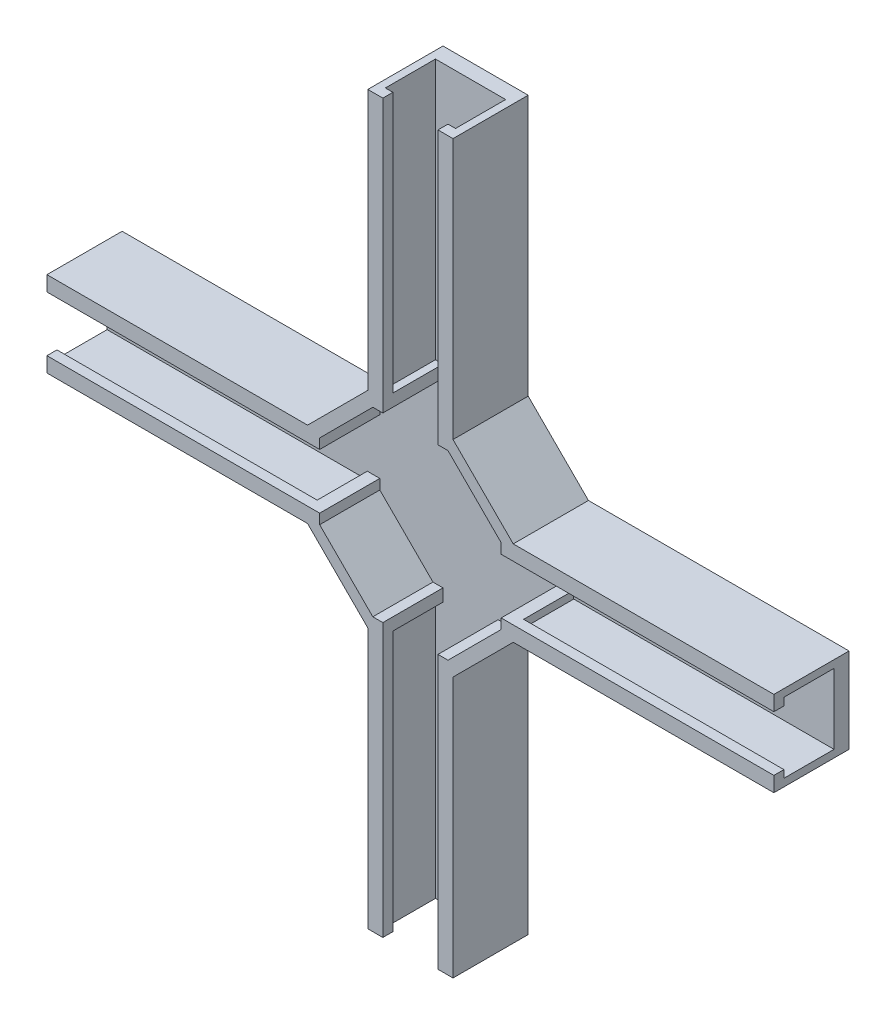
SolidWorks part; units mm, degrees
ref_plane "Спереди" through (0, 0, 0) normal (0, 0, 1) x (1, 0, 0)
ref_plane "Сверху" through (0, 0, 0) normal (0, 1, 0) x (1, 0, 0)
ref_plane "Справа" through (0, 0, 0) normal (1, 0, 0) x (0, 0, -1)
sketch "Эскиз1" plane through (0, 0, 0) normal (0, 0, 1) x (1, 0, 0)
  line L0 (20.5208, 8.5) -> (20.5208, -8.5)
  line L1 (8.5, 20.5208) -> (-8.5, 20.5208)
  line L2 (-8.5, 20.5208) -> (-20.5208, 8.5)
  line L3 (-20.5208, 8.5) -> (-20.5208, -8.5)
  line L4 (-20.5208, -8.5) -> (-8.5, -20.5208)
  line L5 (-8.5, -20.5208) -> (8.5, -20.5208)
  line L6 (8.5, -20.5208) -> (20.5208, -8.5)
  line L7 (20.5208, -8.5) -> (20.5208, 8.5)
  line L8 (20.5208, 8.5) -> (8.5, 20.5208)
  line L9 (20.5208, 8.5) -> (72.5208, 8.5)
  line L10 (20.5208, -8.5) -> (72.5208, -8.5)
  line L11 (72.5208, 8.5) -> (72.5208, -8.5)
  line L12 (-8.5, -20.5208) -> (8.5, -20.5208)
  line L13 (-8.5, -20.5208) -> (-8.5, -72.5208)
  line L14 (8.5, -20.5208) -> (8.5, -72.5208)
  line L15 (-8.5, -72.5208) -> (8.5, -72.5208)
  line L16 (-20.5208, -8.5) -> (-20.5208, 8.5)
  line L17 (-20.5208, -8.5) -> (-72.5208, -8.5)
  line L18 (-20.5208, 8.5) -> (-72.5208, 8.5)
  line L19 (-72.5208, -8.5) -> (-72.5208, 8.5)
  line L20 (-8.5, 20.5208) -> (8.5, 20.5208)
  line L21 (-8.5, 20.5208) -> (-8.5, 72.5208)
  line L22 (8.5, 20.5208) -> (8.5, 72.5208)
  line L23 (-8.5, 72.5208) -> (8.5, 72.5208)
  circle A0 centre (0, 0) radius 20.5208 construction
  dimension "D1" = 52
  dimension "D2" = 52
  dimension "D3" = 52
  dimension "D4" = 52
  dimension "D6" = 17
extrude "Бобышка-Вытянуть1" add sketch "Эскиз1" along normal blind 15 contours L19 L17 L3 L18 | L0 L8 L1 L2 L3 L4 L5 L6 | L23 L21 L1 L22 | L11 L9 L0 L10 | L13 L15 L14 L5
sketch "Эскиз8" plane through (0, 0, 15) normal (0, 0, 1) x (1, 0, 0)
  line L0 (-18.1066, 5.5) -> (-72.5208, 5.5)
  line L1 (18.1066, 7.5) -> (7.5, 18.1066)
  line L2 (7.5, 18.1066) -> (-7.5, 18.1066)
  line L3 (-7.5, 18.1066) -> (-18.1066, 7.5)
  line L4 (-18.1066, 7.5) -> (-18.1066, -7.5)
  line L5 (-18.1066, -7.5) -> (-7.5, -18.1066)
  line L6 (-7.5, -18.1066) -> (7.5, -18.1066)
  line L7 (7.5, -18.1066) -> (18.1066, -7.5)
  line L8 (18.1066, -7.5) -> (18.1066, 7.5)
  line L9 (-18.1066, 5.5) -> (-18.1066, -5.5)
  line L10 (-72.5208, 5.5) -> (-72.5208, -5.5)
  line L11 (-18.1066, -5.5) -> (-72.5208, -5.5)
  line L12 (-72.5208, -8.5) -> (-72.5208, 8.5) construction
  line L13 (-20.5208, 8.5) -> (-72.5208, 8.5) construction
  line L14 (-20.5208, -8.5) -> (-72.5208, -8.5) construction
  line L15 (72.5208, 8.5) -> (72.5208, -8.5) construction
  line L16 (18.1066, -5.5) -> (72.5208, -5.5)
  line L17 (18.1066, -5.5) -> (18.1066, 5.5)
  line L18 (18.1066, 5.5) -> (72.5208, 5.5)
  line L19 (72.5208, -5.5) -> (72.5208, 5.5)
  line L20 (-8.5, 72.5208) -> (8.5, 72.5208) construction
  line L21 (-5.5, 72.5208) -> (5.5, 72.5208)
  line L22 (-5.5, 72.5208) -> (-5.5, 18.1066)
  line L23 (-5.5, 18.1066) -> (5.5, 18.1066)
  line L24 (5.5, 72.5208) -> (5.5, 18.1066)
  line L25 (-8.5, -72.5208) -> (8.5, -72.5208) construction
  line L26 (-5.5, -72.5208) -> (5.5, -72.5208)
  line L27 (-5.5, -72.5208) -> (-5.5, -18.1066)
  line L28 (-5.5, -18.1066) -> (5.5, -18.1066)
  line L29 (5.5, -72.5208) -> (5.5, -18.1066)
  circle A0 centre (0, 0) radius 18.1066 construction
  line M4 (-72.5208, 8.5) -> (-72.5208, -8.5)
  line M8 (-8.5, -72.5208) -> (8.5, -72.5208)
  line M12 (72.5208, -8.5) -> (72.5208, 8.5)
  line M16 (8.5, 72.5208) -> (-8.5, 72.5208)
  dimension "D1" = 15
  dimension "D2" = 0
  dimension "D3" = 3
  dimension "D4" = 3
  dimension "D5" = 3
  dimension "D6" = 3
  dimension "D7" = 3
  dimension "D8" = 3
extrude "Вырез-Вытянуть2" cut sketch "Эскиз8" against normal blind 12 contours L24 L22 L2 M16 | L7 L8 L1 L2 L3 L4 L5 L6 | L18 L8 L16 M12 | L29 L6 L27 M8 | L11 L4 L0 M4
sketch "Эскиз9" plane through (0, 0, 3) normal (0, 0, 1) x (1, 0, 0)
  line L0 (-72.5208, 5.5) -> (-72.5208, 8.5) construction
  line L1 (-72.5208, 7) -> (-20.6018, 7)
  line L2 (-72.5208, 7) -> (-72.5208, -7)
  line L3 (-72.5208, -7) -> (-20.6018, -7)
  line L4 (-20.6018, 7) -> (-20.6018, -7)
  line L5 (-8.5, 72.5208) -> (-5.5, 72.5208) construction
  line L6 (-7, 72.5208) -> (7, 72.5208)
  line L7 (-7, 72.5208) -> (-7, 20.5602)
  line L8 (-7, 20.5602) -> (7, 20.5602)
  line L9 (7, 72.5208) -> (7, 20.5602)
  line L10 (72.5208, 8.5) -> (72.5208, 5.5) construction
  line L11 (72.5208, 7) -> (20.5849, 7)
  line L12 (72.5208, 7) -> (72.5208, -7)
  line L13 (72.5208, -7) -> (20.5849, -7)
  line L14 (20.5849, 7) -> (20.5849, -7)
  line L15 (5.5, -72.5208) -> (8.5, -72.5208) construction
  line L16 (7, -72.5208) -> (-7, -72.5208)
  line L17 (7, -72.5208) -> (7, -20.5724)
  line L18 (7, -20.5724) -> (-7, -20.5724)
  line L19 (-7, -72.5208) -> (-7, -20.5724)
  dimension "D1" = 1.5
  dimension "D2" = 1.5
  dimension "D3" = 1.5
extrude "Вырез-Вытянуть3" cut sketch "Эскиз9" along normal blind 10
